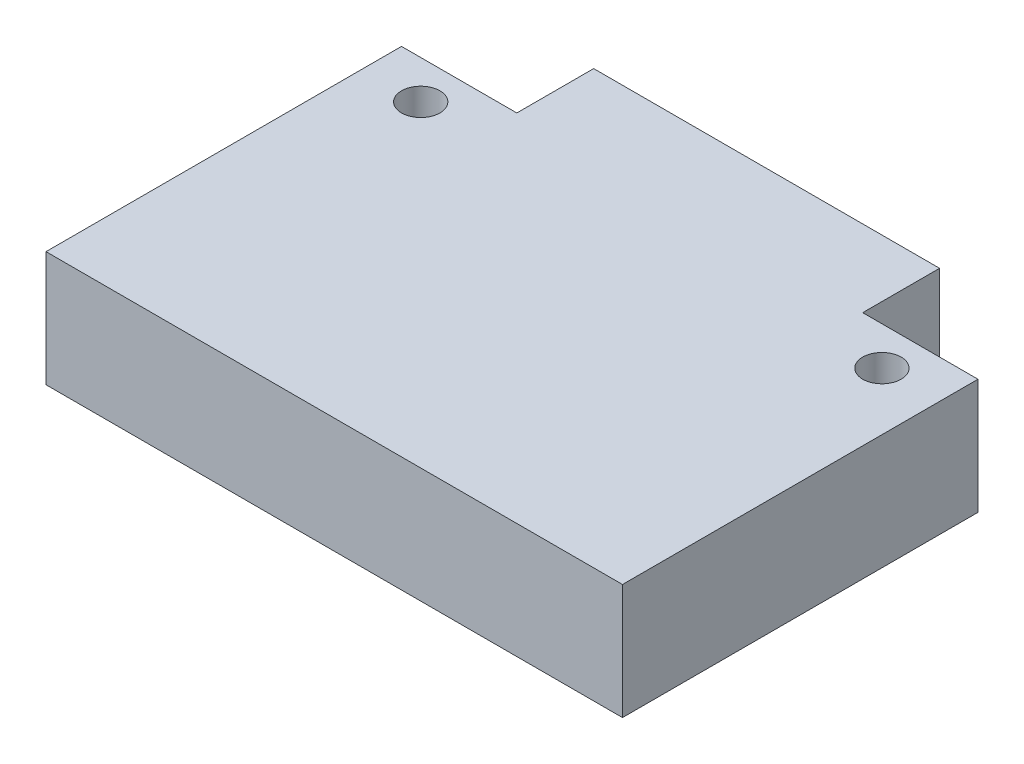
SolidWorks part; units mm, degrees
ref_plane "Front Plane" through (0, 0, 0) normal (0, 0, 1) x (1, 0, 0)
ref_plane "Top Plane" through (0, 0, 0) normal (0, 1, 0) x (1, 0, 0)
ref_plane "Right Plane" through (0, 0, 0) normal (1, 0, 0) x (0, 0, -1)
sketch "Sketch1" plane through (0, 0, 0) normal (0, 1, 0) x (1, 0, 0)
  line L0 (0, 18.5) -> (6, 18.5)
  line L1 (0, 0) -> (30, 0)
  line L2 (0, 0) -> (0, 18.5)
  line L3 (6, 22.5) -> (24, 22.5)
  line L4 (30, 0) -> (30, 18.5)
  line L5 (6, 18.5) -> (6, 22.5)
  line L6 (24, 22.5) -> (24, 18.5)
  line L7 (24, 18.5) -> (30, 18.5)
  dimension "D1" = 6
  dimension "D2" = 6
  dimension "D3" = 30
  dimension "D4" = 22.5
  dimension "D5" = 4
extrude "Boss-Extrude1" add sketch "Sketch1" along normal blind 6
sketch "Sketch2" plane through (0, 6, 0) normal (0, 1, 0) x (1, 0, 0)
  line L0 (6, 18.5) -> (0, 18.5) construction
  line L1 (0, 18.5) -> (0, 0) construction
  line L2 (30, 0) -> (30, 18.5) construction
  circle A0 centre (3, 16.5) radius 1
  circle A1 centre (27, 16.5) radius 1
  dimension "D1" = 2
  dimension "D2" = 2
  dimension "D3" = 3
  dimension "D4" = 3
extrude "Cut-Extrude1" cut sketch "Sketch2" against normal through all
